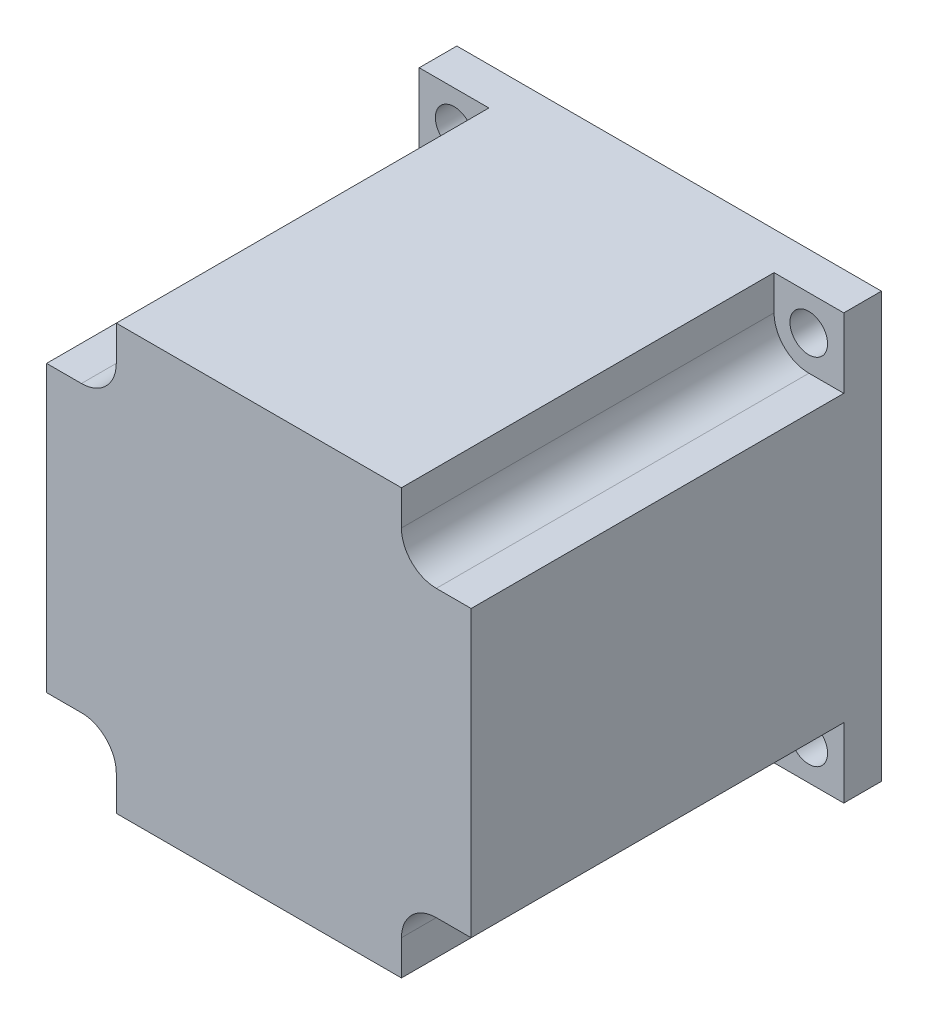
SolidWorks part; units mm, degrees
ref_plane "前视基准面" through (0, 0, 0) normal (0, 0, 1) x (1, 0, 0)
ref_plane "上视基准面" through (0, 0, 0) normal (0, 1, 0) x (1, 0, 0)
ref_plane "右视基准面" through (0, 0, 0) normal (1, 0, 0) x (0, 0, -1)
sketch "草图1" plane through (0, 0, 0) normal (0, 0, 1) x (1, 0, 0)
  line L0 (23.55, -23.55) -> (-23.55, -23.55) construction
  line L1 (-28.2, -28.2) -> (28.2, -28.2)
  line L2 (-28.2, -28.2) -> (-28.2, 28.2)
  line L3 (-28.2, 28.2) -> (28.2, 28.2)
  line L4 (28.2, -28.2) -> (28.2, 28.2)
  line L5 (-28.2, -28.2) -> (28.2, 28.2) construction
  line L6 (-28.2, 28.2) -> (28.2, -28.2) construction
  circle A6 centre (23.55, -23.55) radius 2.5
  circle A7 centre (-23.55, -23.55) radius 2.5
  circle A8 centre (23.55, 23.55) radius 2.5
  circle A9 centre (-23.55, 23.55) radius 2.5
  point P0 (0, 0)
  dimension "D1" = 56.4
  dimension "D2" = 56.4
extrude "凸台-拉伸1" add sketch "草图1" along normal blind 54.5
sketch "草图2" plane through (0, 0, 0) normal (0, 0, -1) x (-1, 0, 0)
  circle A0 centre (0, 0) radius 4
  dimension "D1" = 8
extrude "凸台-拉伸2" add sketch "草图2" along normal blind 22
sketch "草图3" plane through (0, 0, -22) normal (0, 0, -1) x (-1, 0, 0)
  line L1 (1.9365, -3.5) -> (-1.9365, -3.5)
  circle A0 centre (0, 0) radius 4 construction
  arc A2 (-1.9365, -3.5) -> (1.9365, -3.5) centre (0, 0) ccw
extrude "切除-拉伸1" cut sketch "草图3" against normal blind 18
sketch "草图4" plane through (0, 0, 0) normal (0, 0, -1) x (-1, 0, 0)
  circle A0 centre (0, 0) radius 19.05
  dimension "D1" = 38.1
extrude "凸台-拉伸3" add sketch "草图4" along normal blind 2
sketch "草图5" plane through (0, 0, 54.5) normal (0, 0, 1) x (1, 0, 0)
  line L0 (23.57, 18.94) -> (28.2, 18.94)
  line L1 (28.2, -28.2) -> (28.2, 28.2) construction
  line L2 (18.94, 23.57) -> (18.94, 28.2)
  line L3 (28.2, 28.2) -> (-28.2, 28.2) construction
  line L4 (18.94, 28.2) -> (28.2, 28.2)
  line L5 (28.2, 28.2) -> (28.2, 18.94)
  line L6 (18.94, -23.57) -> (18.94, -28.2)
  line L7 (23.57, -18.94) -> (28.2, -18.94)
  line L8 (28.2, -18.94) -> (28.2, -28.2)
  line L9 (28.2, -28.2) -> (18.94, -28.2)
  line L10 (-23.57, -18.94) -> (-28.2, -18.94)
  line L11 (-18.94, -23.57) -> (-18.94, -28.2)
  line L12 (-18.94, -28.2) -> (-28.2, -28.2)
  line L13 (-28.2, -28.2) -> (-28.2, -18.94)
  line L14 (-18.94, 23.57) -> (-18.94, 28.2)
  line L15 (-23.57, 18.94) -> (-28.2, 18.94)
  line L16 (-28.2, 18.94) -> (-28.2, 28.2)
  line L17 (-28.2, 28.2) -> (-18.94, 28.2)
  circle A0 centre (23.57, 23.57) radius 4.63 construction
  arc A1 (18.94, 23.57) -> (23.57, 18.94) centre (23.57, 23.57) ccw
  arc A2 (23.57, -18.94) -> (18.94, -23.57) centre (23.57, -23.57) ccw
  arc A3 (-18.94, -23.57) -> (-23.57, -18.94) centre (-23.57, -23.57) ccw
  arc A4 (-23.57, 18.94) -> (-18.94, 23.57) centre (-23.57, 23.57) ccw
  dimension "D1" = 4
extrude "切除-拉伸2" cut sketch "草图5" against normal blind 49.5
